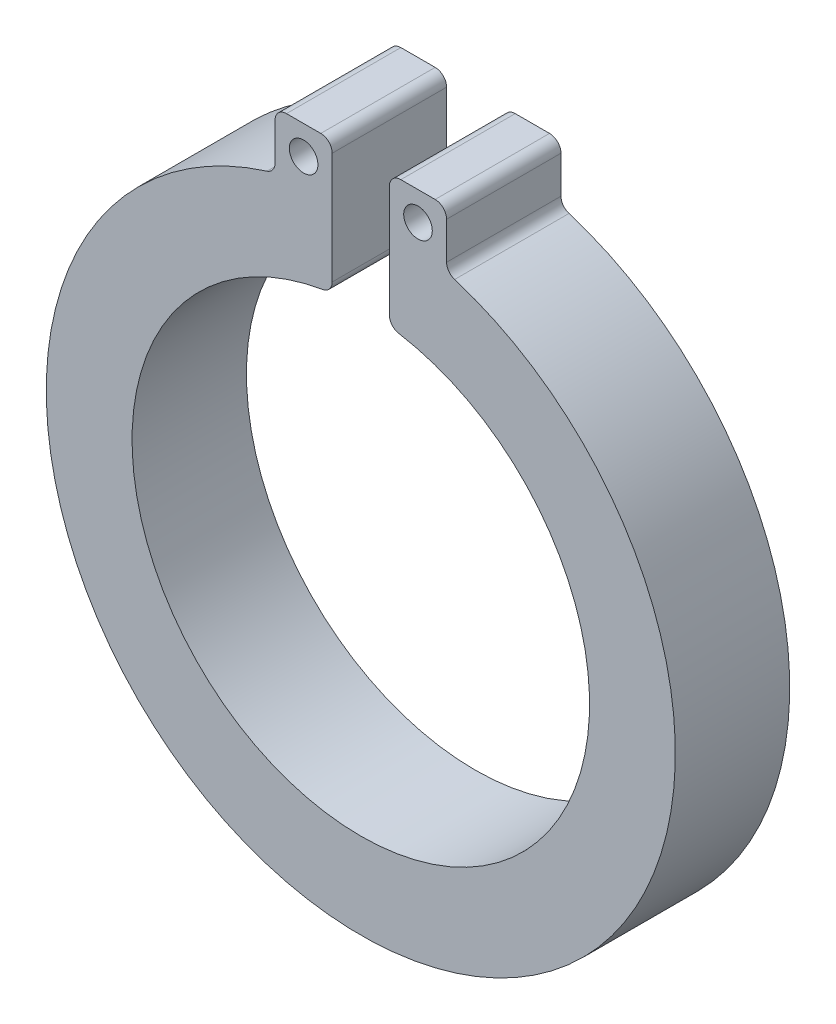
SolidWorks part; units mm, degrees
material "AISI 304"
ref_plane "Front Plane" through (0, 0, 0) normal (0, 0, 1) x (1, 0, 0)
ref_plane "Top Plane" through (0, 0, 0) normal (0, 1, 0) x (1, 0, 0)
ref_plane "Right Plane" through (0, 0, 0) normal (1, 0, 0) x (0, 0, -1)
sketch "Sketch1" plane through (0, 0, 0) normal (0, 0, 1) x (1, 0, 0)
  line L0 (-0.25, 3.1458) -> (-0.25, 1.9843)
  line L1 (0.25, 3.1458) -> (0.25, 1.9843)
  line L3 (-0.25, 3.1458) -> (-0.75, 3.1458)
  line L4 (-0.75, 3.1458) -> (-0.75, 2.6458)
  line L5 (0, -55) -> (0, 55) construction
  line L7 (0.75, 3.1458) -> (0.75, 2.6458)
  line L8 (0.25, 3.1458) -> (0.75, 3.1458)
  arc A0 (-0.25, 1.9843) -> (0.25, 1.9843) centre (0, 0) ccw
  arc A1 (-0.75, 2.6458) -> (0.75, 2.6458) centre (0, 0) ccw
  circle A2 centre (-0.5, 2.8958) radius 0.125
  circle A3 centre (0.5, 2.8958) radius 0.125
  point P14 (0.5, 2.8958)
  point P15 (-0.5, 2.8958)
  dimension "D1" = 4
  dimension "D2" = 5.5
  dimension "D10" = 0.25
  dimension "D3" = 0.5
  dimension "D4" = 0.5
  dimension "D5" = 0.5
  dimension "D6" = 0.25
  dimension "D7" = 0.25
  dimension "D8" = 0.25
  dimension "D9" = 0.25
extrude "Boss-Extrude1" add sketch "Sketch1" along normal blind 1
fillet "Fillet1" radius 0.1 8 edges at (-0.75, 3.1458, 0.5) (-0.25, 3.1458, 0.5) (0.25, 3.1458, 0.5) (0.75, 3.1458, 0.5) (0.75, 2.6458, 0.5) (-0.75, 2.6458, 0.5) (0.25, 1.9843, 0.5) (-0.25, 1.9843, 0.5)
